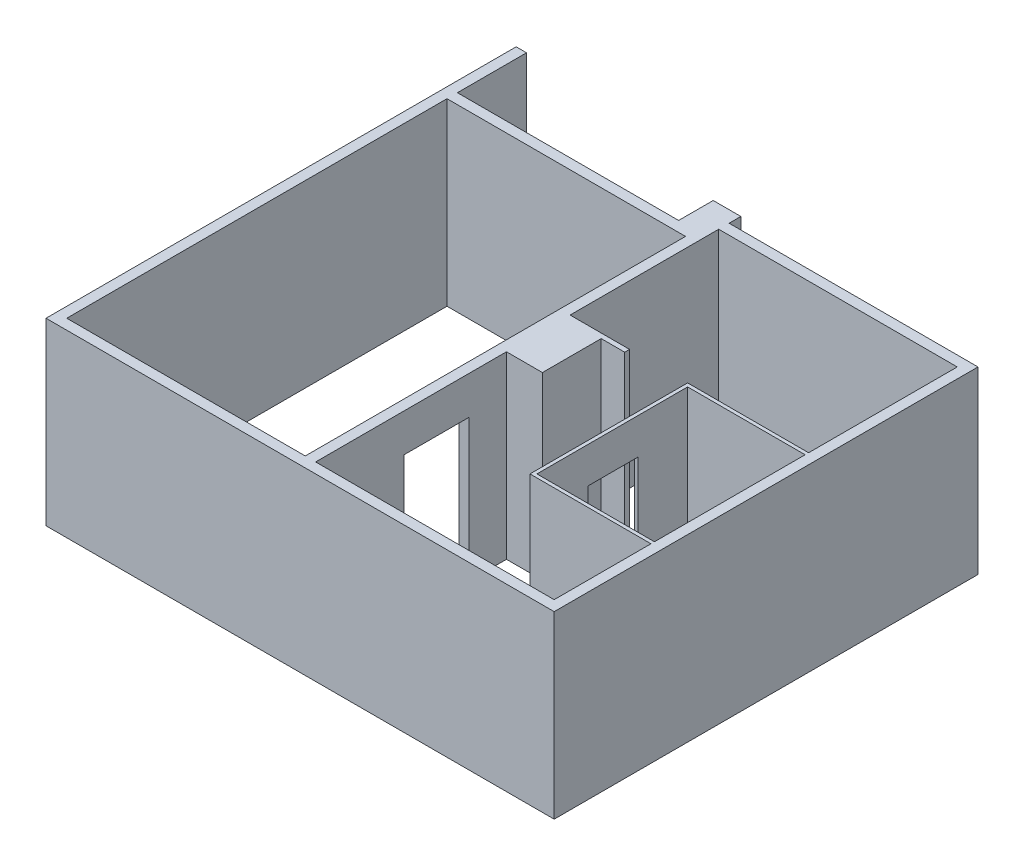
SolidWorks part; units mm, degrees
ref_plane "Спереди" through (0, 0, 0) normal (0, 0, 1) x (1, 0, 0)
ref_plane "Сверху" through (0, 0, 0) normal (0, 1, 0) x (1, 0, 0)
ref_plane "Справа" through (0, 0, 0) normal (1, 0, 0) x (0, 0, -1)
sketch "Эскиз1" plane through (0, 0, 0) normal (0, 1, 0) x (1, 0, 0)
  line L0 (-3600, 2970) -> (-3600, 839.3883)
  line L2 (-3600, 839.3883) -> (-3600, -3830)
  line L3 (-3600, -3830) -> (3750, -3830)
  line L4 (3750, -3830) -> (3750, 2300)
  line L5 (3750, 2300) -> (150, 2300)
  line L6 (150, 2300) -> (150, 2470)
  line L7 (150, 2470) -> (-250, 2470)
  line L8 (-250, 2470) -> (-250, 1970)
  line L9 (-250, 1970) -> (-3450, 1970)
  line L10 (-3450, 1970) -> (-3450, 2970)
  line L11 (-3450, 2970) -> (-3600, 2970)
  line L12 (-3450, 1820) -> (-3450, -3680)
  line L13 (-3450, -3680) -> (0, -3680)
  line L14 (0, -3680) -> (0, 1820)
  line L15 (0, 1820) -> (-3450, 1820)
  line L16 (150, 2150) -> (150, 0)
  line L17 (150, -3680) -> (3600, -3680)
  line L18 (3600, -3680) -> (3600, -2280)
  line L19 (3600, 2150) -> (150, 2150)
  line L20 (3600, -2280) -> (1850, -2280)
  line L21 (1850, -2280) -> (1850, 0)
  line L22 (1850, 0) -> (3600, 0)
  line L23 (3600, -50) -> (1900, -50)
  line L24 (1900, -50) -> (1900, -2230)
  line L25 (1900, -2230) -> (3600, -2230)
  line L26 (3600, 0) -> (3600, 2150)
  line L27 (3600, -2230) -> (3600, -50)
  line L28 (150, 0) -> (1010, 0)
  line L29 (1010, 0) -> (1010, -70)
  line L30 (1010, -70) -> (670, -70)
  line L31 (670, -70) -> (670, -920)
  line L32 (670, -920) -> (150, -920)
  line L33 (150, -920) -> (150, -3680)
  line L34 (3600, 0) -> (3600, -50) construction
  line L35 (3600, -2230) -> (3600, -2280) construction
  dimension "D1" = 3450
  dimension "D2" = 3450
  dimension "D3" = 150
  dimension "D4" = 150
  dimension "D5" = 150
  dimension "D6" = 150
  dimension "D7" = 1700
  dimension "D8" = 2180
  dimension "D9" = 5500
  dimension "D10" = 50
  dimension "D11" = 1400
  dimension "D12" = 2150
  dimension "D13" = 520
  dimension "D14" = 850
  dimension "D15" = 340
  dimension "D16" = 70
  dimension "D17" = 150
  dimension "D18" = 150
  dimension "D19" = 2760
  dimension "D20" = 3200
  dimension "D21" = 1000
  dimension "D22" = 500
extrude "Бобышка-Вытянуть1" add sketch "Эскиз1" along normal blind 2600
sketch "Sketch1" plane through (0, 0, 0) normal (-1, 0, 0) x (0, 0, 1)
  line L0 (3680, 0) -> (-1820, 0) construction
  line L1 (2400, 0) -> (1460, 0)
  line L2 (2400, 0) -> (2400, 2050)
  line L3 (2400, 2050) -> (1460, 2050)
  line L4 (1460, 0) -> (1460, 2050)
  line L5 (3680, 2600) -> (3680, 0) construction
  dimension "D1" = 2050
  dimension "D2" = 1280
  dimension "D3" = 940
extrude "Cut-Extrude1" cut sketch "Sketch1" against normal up to surface (150 mm away) up to face at (150, 1300, 2300)
sketch "Sketch2" plane through (1850, 0, 0) normal (-1, 0, 0) x (0, 0, 1)
  line L5 (770, 130) -> (1490, 130)
  line L6 (770, 130) -> (770, 2080)
  line L7 (770, 2080) -> (1490, 2080)
  line L8 (1490, 130) -> (1490, 2080)
  line L9 (2280, 2600) -> (2280, 0) construction
  line L10 (2280, 0) -> (0, 0) construction
  dimension "D1" = 790
  dimension "D2" = 720
  dimension "D3" = 1950
  dimension "D4" = 130
extrude "Cut-Extrude2" cut sketch "Sketch2" against normal up to surface (50 mm away) up to face at (1900, 1300, 1140)
